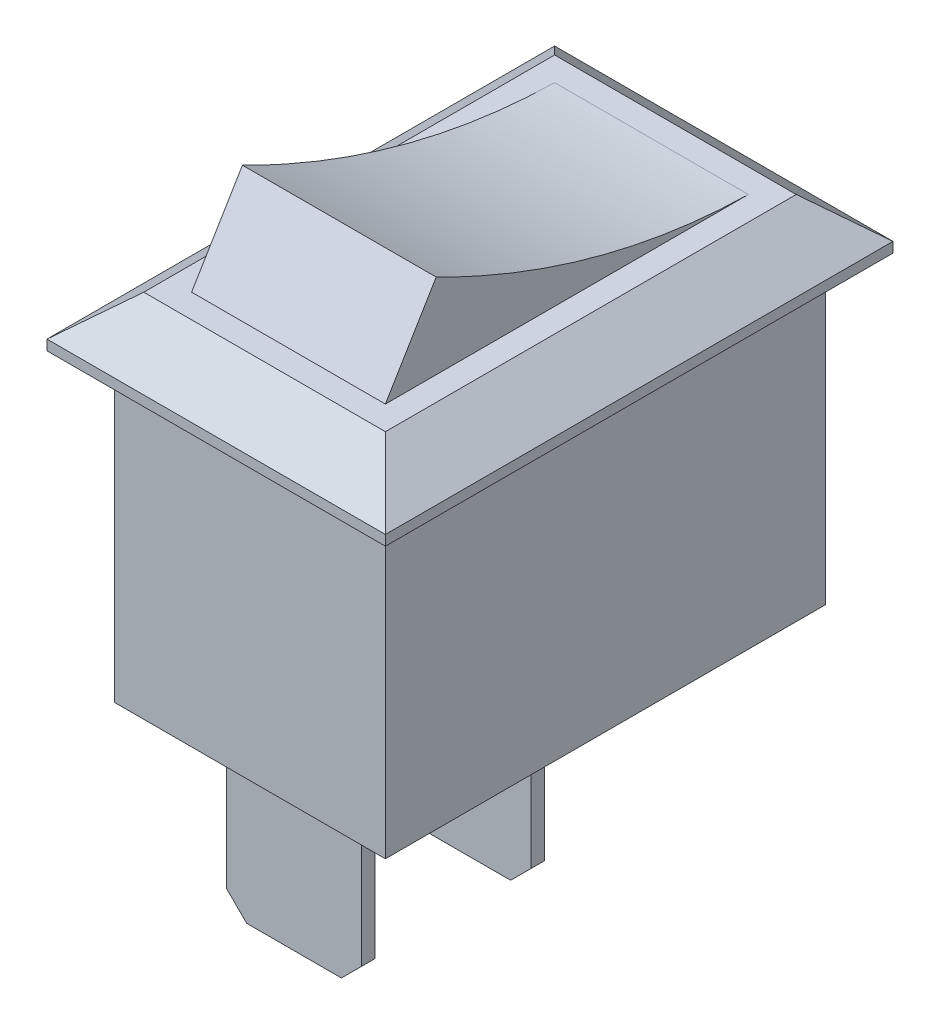
SolidWorks part; units mm, degrees
material "Custom Plastic"
ref_plane "Front Plane" through (0, 0, 0) normal (0, 0, 1) x (1, 0, 0)
ref_plane "Top Plane" through (0, 0, 0) normal (0, 1, 0) x (1, 0, 0)
ref_plane "Right Plane" through (0, 0, 0) normal (1, 0, 0) x (0, 0, -1)
sketch "Sketch1" plane through (0, 0, 0) normal (0, 1, 0) x (1, 0, 0)
  line L1 (4, 6.5) -> (-4, 6.5)
  line L2 (4, 6.5) -> (4, -6.5)
  line L3 (4, -6.5) -> (-4, -6.5)
  line L4 (-4, 6.5) -> (-4, -6.5)
  point P0 (0, 0)
extrude "Boss-Extrude1" add sketch "Sketch1" along normal blind 9
sketch "Sketch2" plane through (0, 9, 0) normal (0, 1, 0) x (1, 0, 0)
  line L1 (-5, -7.5) -> (5, -7.5)
  line L2 (-5, -7.5) -> (-5, 7.5)
  line L3 (-5, 7.5) -> (5, 7.5)
  line L4 (5, -7.5) -> (5, 7.5)
  point P0 (0, 0)
extrude "Boss-Extrude2" add sketch "Sketch2" along normal blind 1.5
chamfer "Chamfer1" distance 1.2 angle 50 4 edges at (0, 10.5, -7.5) (-5, 10.5, 0) (0, 10.5, 7.5) (5, 10.5, 0)
sketch "Sketch3" plane through (0, 10.5, 0) normal (0, 1, 0) x (1, 0, 0)
  line L3 (-2.8628, 5.3628) -> (2.8628, 5.3628)
  line L4 (-2.8628, 5.3628) -> (-2.8628, -5.3628)
  line L5 (-2.8628, -5.3628) -> (2.8628, -5.3628)
  line L6 (2.8628, 5.3628) -> (2.8628, -5.3628)
extrude "Boss-Extrude3" add sketch "Sketch3" along normal blind 2.5
sketch "Sketch4" plane through (-2.8628, 0, 0) normal (-1, 0, 0) x (0, 0, 1)
  line L0 (5.3628, 13) -> (3.8628, 13)
  line L1 (-5.3628, 13) -> (5.3628, 13) construction
  line L2 (3.8628, 13) -> (5.3628, 10.5)
  line L3 (5.3628, 10.5) -> (5.3628, 13)
extrude "Cut-Extrude2" cut sketch "Sketch4" against normal blind 10
sketch "Sketch5" plane through (-2.8628, 0, 0) normal (-1, 0, 0) x (0, 0, 1)
  line L0 (-5.3628, 10.5) -> (-5.3628, 13)
  line L1 (-5.3628, 13) -> (3.8628, 13)
  spline S0 degree 2 poles (3.8628, 13) (-0.8864, 10.5856) (-5.3628, 10.5) knots 0 0 0 0.869788 0.869788 0.869788
extrude "Cut-Extrude3" cut sketch "Sketch5" against normal blind 10
sketch "Sketch6" plane through (0, 0, 0) normal (0, -1, 0) x (1, 0, 0)
  line L6 (-2, 4.8) -> (2, 4.8)
  line L7 (-2, 4.8) -> (-2, 5.2)
  line L8 (-2, 5.2) -> (2, 5.2)
  line L9 (2, 4.8) -> (2, 5.2)
  point P9 (0, 5)
extrude "Boss-Extrude4" add sketch "Sketch6" along normal blind 5
chamfer "Chamfer2" distance 0.6 angle 45 2 edges at (2, -5, 5) (-2, -5, 5)
pattern_linear "LPattern1" count 2 spacing 5 along (0, 0, -1) of "Boss-Extrude4"
chamfer "Chamfer3" distance 0.6 angle 45 2 edges at (2, -5, 0) (-2, -5, 0)
